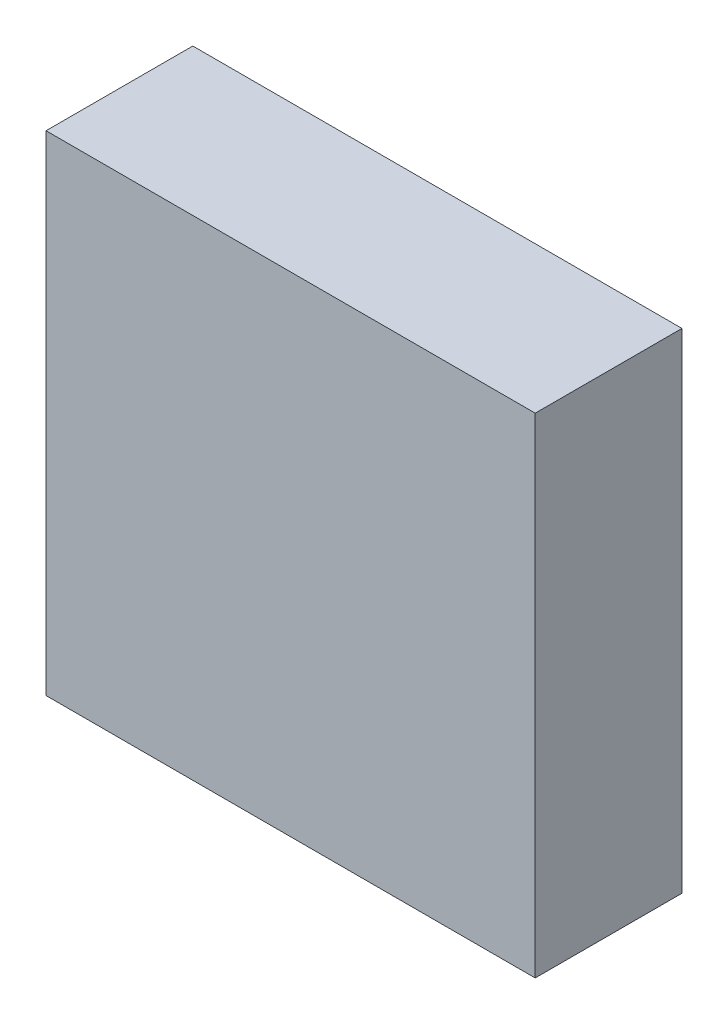
SolidWorks part; units mm, degrees
ref_plane "前视基准面" through (0, 0, 0) normal (0, 0, 1) x (1, 0, 0)
ref_plane "上视基准面" through (0, 0, 0) normal (0, 1, 0) x (1, 0, 0)
ref_plane "右视基准面" through (0, 0, 0) normal (1, 0, 0) x (0, 0, -1)
sketch "草图1" plane through (0, 0, 0) normal (0, 0, 1) x (1, 0, 0)
  line L1 (0, 0) -> (40, 0)
  line L2 (0, 0) -> (0, -40)
  line L3 (0, -40) -> (40, -40)
  line L4 (40, 0) -> (40, -40)
  dimension "D1" = 40
  dimension "D2" = 40
extrude "凸台-拉伸1" add sketch "草图1" along normal blind 12
